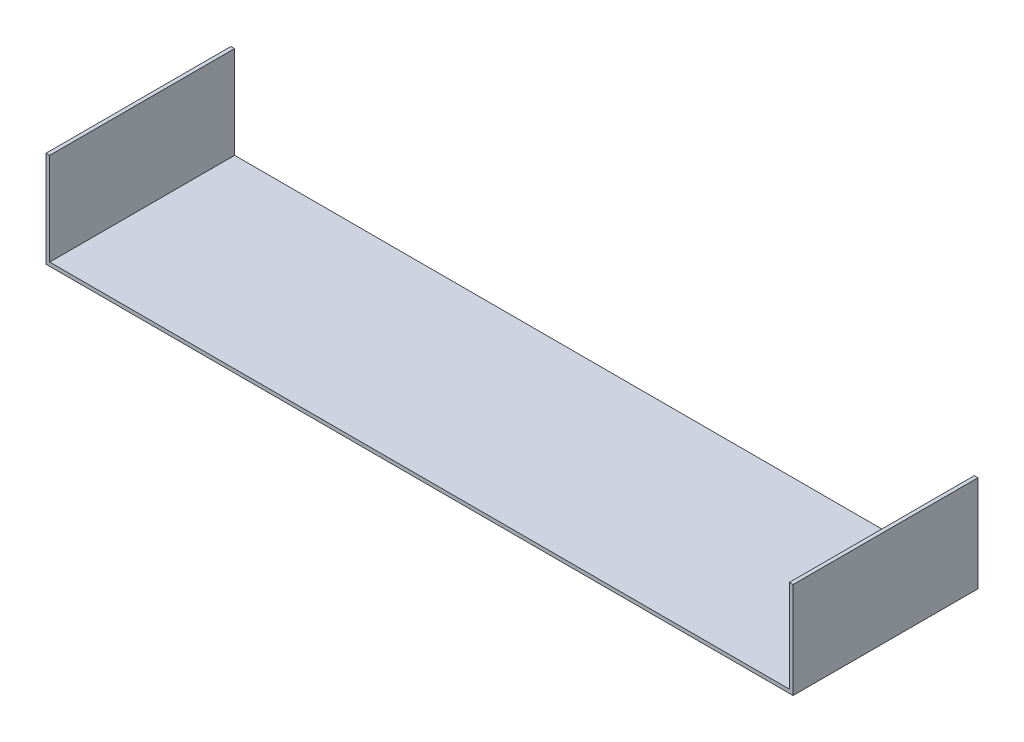
SolidWorks part; units mm, degrees
ref_plane "Front Plane" through (0, 0, 0) normal (0, 0, 1) x (1, 0, 0)
ref_plane "Top Plane" through (0, 0, 0) normal (0, 1, 0) x (1, 0, 0)
ref_plane "Right Plane" through (0, 0, 0) normal (1, 0, 0) x (0, 0, -1)
sketch "Sketch2" plane through (0, 0, 0) normal (0, 0, 1) x (1, 0, 0)
  line L0 (0, 0) -> (0, -5000)
  line L1 (0, -5000) -> (40000, -5000)
  line L2 (40000, -5000) -> (40000, 0)
  line L3 (-200, 0) -> (-200, -5200)
  line L4 (-200, -5200) -> (40200, -5200)
  line L5 (40200, -5200) -> (40200, 0)
  line L6 (-200, 0) -> (0, 0)
  line L7 (40000, 0) -> (40200, 0)
extrude "Boss-Extrude1" add sketch "Sketch2" against normal blind 10000
